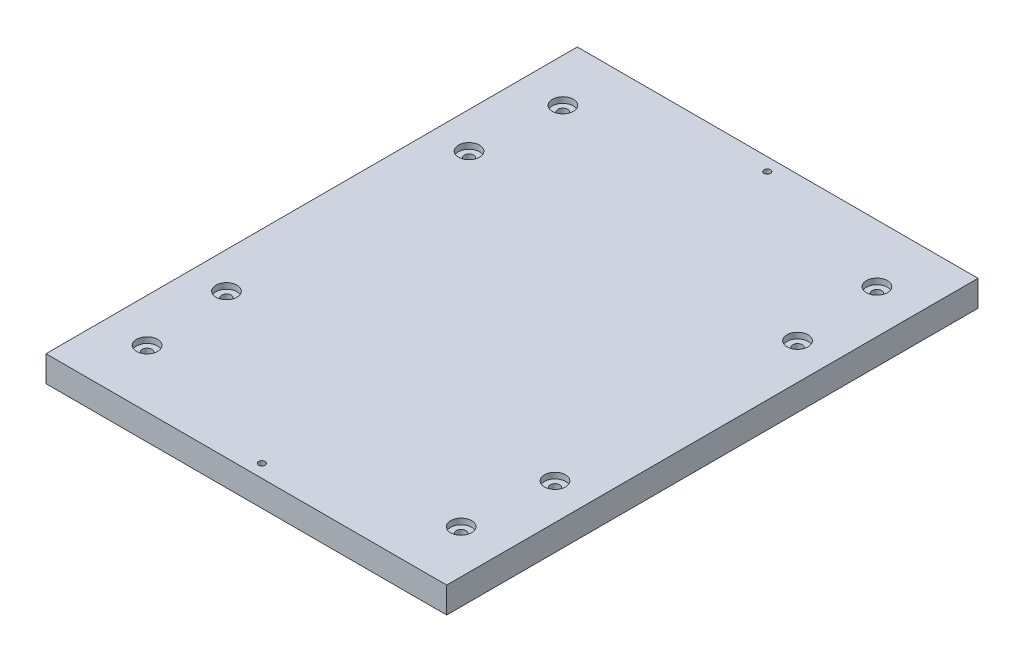
SolidWorks part; units mm, degrees
ref_plane "Front Plane" through (0, 0, 0) normal (0, 0, 1) x (1, 0, 0)
ref_plane "Top Plane" through (0, 0, 0) normal (0, 1, 0) x (1, 0, 0)
ref_plane "Right Plane" through (0, 0, 0) normal (1, 0, 0) x (0, 0, -1)
sketch "Sketch1" plane through (0, 0, 0) normal (0, 1, 0) x (1, 0, 0)
  line L1 (-138.775, 184) -> (138.775, 184)
  line L2 (-138.775, 184) -> (-138.775, -184)
  line L3 (-138.775, -184) -> (138.775, -184)
  line L4 (138.775, 184) -> (138.775, -184)
  point P4 (-138.775, 0)
  point P6 (0, 184)
  dimension "D1" = 277.55
  dimension "D3" = 368
extrude "Boss-Extrude1" add sketch "Sketch1" along normal blind 39
ref_plane "Plane1" through (-138.775, 0, 0) normal (-1, 0, 0) x (0, 0, 1)
ref_plane "Plane2" through (0, 0, 184) normal (0, 0, 1) x (1, 0, 0)
sketch "Sketch2" plane through (0, 0, 0) normal (0, 1, 0) x (1, 0, 0)
  line L22 (138.775, 184) -> (-138.775, 184) construction
  line L23 (99.775, 123.5) -> (-99.775, 123.5)
  line L24 (99.775, 123.5) -> (99.775, -123.5)
  line L25 (99.775, -123.5) -> (-99.775, -123.5)
  line L26 (-99.775, 123.5) -> (-99.775, -123.5)
  line L27 (138.775, -184) -> (138.775, 184) construction
  dimension "D1" = 199.55
  dimension "D2" = 247
  dimension "D3" = 60.5
  dimension "D4" = 39
extrude "Cut-Extrude1" cut sketch "Sketch2" along normal blind 7 flip side to cut
sketch "Sketch3" plane through (0, 0, 0) normal (0, 1, 0) x (1, 0, 0)
  line L0 (138.775, -184) -> (138.775, 184) construction
  line L1 (124.775, -162.5) -> (-124.775, -162.5)
  line L2 (124.775, -162.5) -> (124.775, 162.5)
  line L3 (124.775, 162.5) -> (-124.775, 162.5)
  line L4 (-124.775, -162.5) -> (-124.775, 162.5)
  line L5 (138.775, 184) -> (-138.775, 184) construction
  point P4 (124.775, 0)
  point P7 (138.775, 0)
  point P8 (0, 162.5)
  point P11 (0, 184)
  dimension "D1" = 325
  dimension "D2" = 249.55
extrude "Cut-Extrude2" cut sketch "Sketch3" along normal blind 21 flip side to cut
ref_plane "Plane4" through (0, 21, 0) normal (0, -1, 0) x (-1, 0, 0)
ref_plane "Plane3" through (0, 39, 0) normal (0, 1, 0) x (1, 0, 0)
sketch "Sketch5" plane through (0, 39, 0) normal (0, 1, 0) x (1, 0, 0)
  line L0 (0, 0) -> (0, 184) construction
  line L1 (138.775, 184) -> (-138.775, 184) construction
  line L2 (-138.775, 184) -> (-138.775, -184) construction
  line L3 (0, 0) -> (-138.775, 0) construction
  circle A2 centre (-113.775, 84) radius 3
  circle A3 centre (-108.775, 144) radius 3
  circle A4 centre (-108.775, -144) radius 3
  circle A5 centre (-113.775, -84) radius 3
  circle A6 centre (113.775, -84) radius 3
  circle A7 centre (108.775, -144) radius 3
  circle A8 centre (108.775, 144) radius 3
  circle A9 centre (113.775, 84) radius 3
  dimension "D3" = 6
  dimension "D4" = 6
  dimension "D1" = 40
  dimension "D2" = 30
  dimension "D5" = 60
  dimension "D6" = 25
hole_wizard "CBORE for M6 Hex Head Bolt1" positions "Sketch6" profile "Sketch7" counterbore size "M6" standard "ISO" end condition through all
sketch "Sketch6" plane through (0, 39, 0) normal (0, 1, 0) x (1, 0, 0)
  point P0 (-108.775, -144)
  point P3 (-113.775, -84)
  point P6 (-113.775, 84)
  point P9 (-108.775, 144)
  point P12 (108.775, 144)
  point P15 (113.775, 84)
  point P18 (113.775, -84)
  point P21 (108.775, -144)
sketch "Sketch7" plane through (-108.775, 39, 144) normal (1, 0, 0) x (0, 0, 1)
  line L0 (0, 0) -> (0, 39)
  line L1 (0, 39) -> (3.3, 39)
  line L3 (3.3, 39) -> (3.3, 4)
  line L4 (3.3, 4) -> (7.2735, 4)
  line L5 (7.2735, 4) -> (7.2735, 0)
  line L7 (7.2735, 0) -> (0, 0)
  line L11 (0, -6.35) -> (0, 107.95) construction
  dimension "Thru Hole Dia." = 6.6
  dimension "Thru Hole Depth" = 39
  dimension "C'Bore Dia." = 14.547
  dimension "C'Bore Depth" = 4
sketch "Sketch8" plane through (0, 21, 0) normal (0, 1, 0) x (1, 0, 0)
  line L1 (124.275, 162.5) -> (-124.275, 162.5)
  line L2 (124.775, 162) -> (124.775, -162)
  line L3 (124.275, -162.5) -> (-124.275, -162.5)
  line L4 (-124.775, 162) -> (-124.775, -162)
  line L5 (-128.775, -166.5) -> (128.775, -166.5)
  line L6 (-128.775, -166.5) -> (-128.775, 166.5)
  line L7 (-128.775, 166.5) -> (128.775, 166.5)
  line L8 (128.775, -166.5) -> (128.775, 166.5)
  arc A0 (124.775, -162) -> (124.275, -162.5) centre (124.275, -162) cw
  arc A1 (-124.275, -162.5) -> (-124.775, -162) centre (-124.275, -162) cw
  arc A2 (124.275, 162.5) -> (124.775, 162) centre (124.275, 162) cw
  arc A3 (-124.275, 162.5) -> (-124.775, 162) centre (-124.275, 162) ccw
  point P14 (-124.775, -162.5)
  point P17 (124.775, 162.5)
  dimension "D5" = 0.5
  dimension "D1" = 4
  dimension "D2" = 4
  dimension "D3" = 4
  dimension "D4" = 4
extrude "Cut-Extrude3" cut sketch "Sketch8" along normal blind 2.3
sketch "Sketch9" plane through (0, 21, 0) normal (0, -1, 0) x (-1, 0, 0)
  line L0 (138.775, -184) -> (-138.775, -184) construction
  line L1 (0, 0) -> (138.775, 0) construction
  line L2 (138.775, 184) -> (138.775, -184) construction
  line L5 (-138.775, -184) -> (-138.775, 184) construction
  circle A1 centre (-1.775, -175) radius 2.25
  circle A2 centre (-1.775, 175) radius 2.25
  dimension "D4" = 9
  dimension "D5" = 137
  dimension "D6" = 4.5
extrude "Cut-Extrude4" cut sketch "Sketch9" against normal through all
